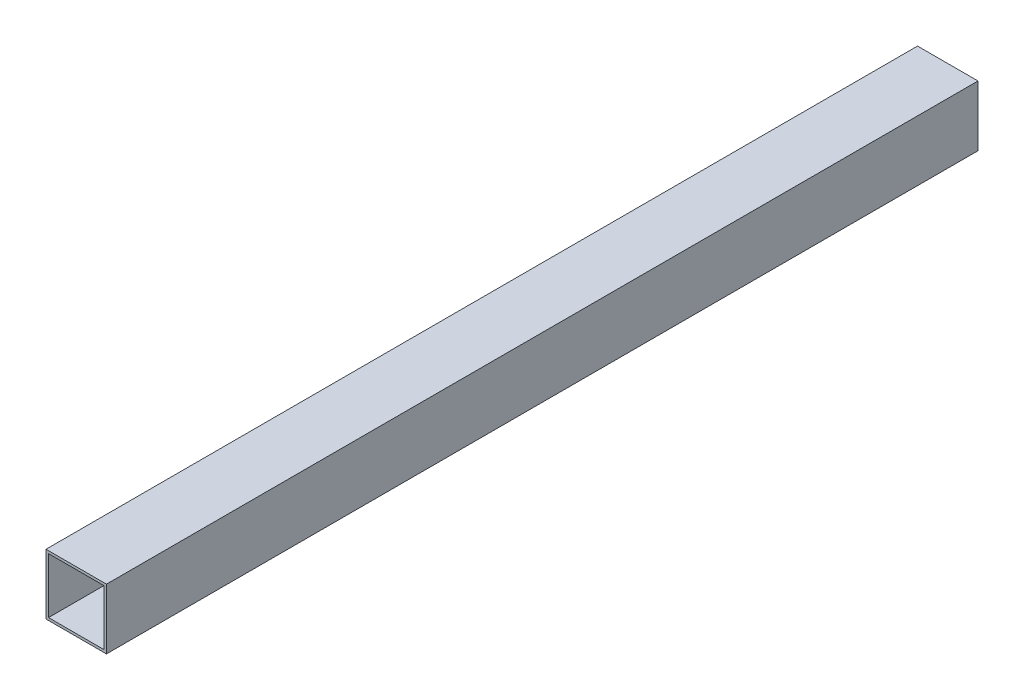
SolidWorks part; units mm, degrees
material "Custom Plastic"
ref_plane "Front Plane" through (0, 0, 0) normal (0, 0, 1) x (1, 0, 0)
ref_plane "Top Plane" through (0, 0, 0) normal (0, 1, 0) x (1, 0, 0)
ref_plane "Right Plane" through (0, 0, 0) normal (1, 0, 0) x (0, 0, -1)
sketch "Sketch2" plane through (0, 0, 0) normal (0, 0, 1) x (1, 0, 0)
  line L9 (-40.7297, 18.631) -> (35.4703, 18.631)
  line L10 (-40.7297, 18.631) -> (-40.7297, -57.569)
  line L11 (-40.7297, -57.569) -> (35.4703, -57.569)
  line L12 (35.4703, 18.631) -> (35.4703, -57.569)
extrude "Boss-Extrude1" add sketch "Sketch2" along normal blind 1098.55 contours L10 L11 L12 L9
sketch "Sketch3" plane through (0, 0, 1098.55) normal (0, 0, 1) x (1, 0, 0)
  line L0 (35.4703, 18.631) -> (35.4703, -57.569) construction
  line L1 (-40.7297, -57.569) -> (35.4703, -57.569) construction
  line L2 (-40.7297, 18.631) -> (-40.7297, -57.569) construction
  line L3 (-40.7297, 18.631) -> (35.4703, 18.631) construction
  line L4 (35.4703, 18.631) -> (35.4703, -57.569)
  line L5 (-40.7297, -57.569) -> (35.4703, -57.569)
  line L6 (-40.7297, 18.631) -> (-40.7297, -57.569)
  line L7 (-40.7297, 18.631) -> (35.4703, 18.631)
  line L9 (-37.5547, 15.456) -> (32.2953, 15.456)
  line L10 (-37.5547, 15.456) -> (-37.5547, -54.394)
  line L11 (-37.5547, -54.394) -> (32.2953, -54.394)
  line L12 (32.2953, 15.456) -> (32.2953, -54.394)
  dimension "D1" = 69.85
  dimension "D2" = 69.85
  dimension "D3" = 3.175
  dimension "D4" = 3.175
extrude "Cut-Extrude1" cut sketch "Sketch3" against normal blind 1098.55 contours L10 L11 L12 L9
